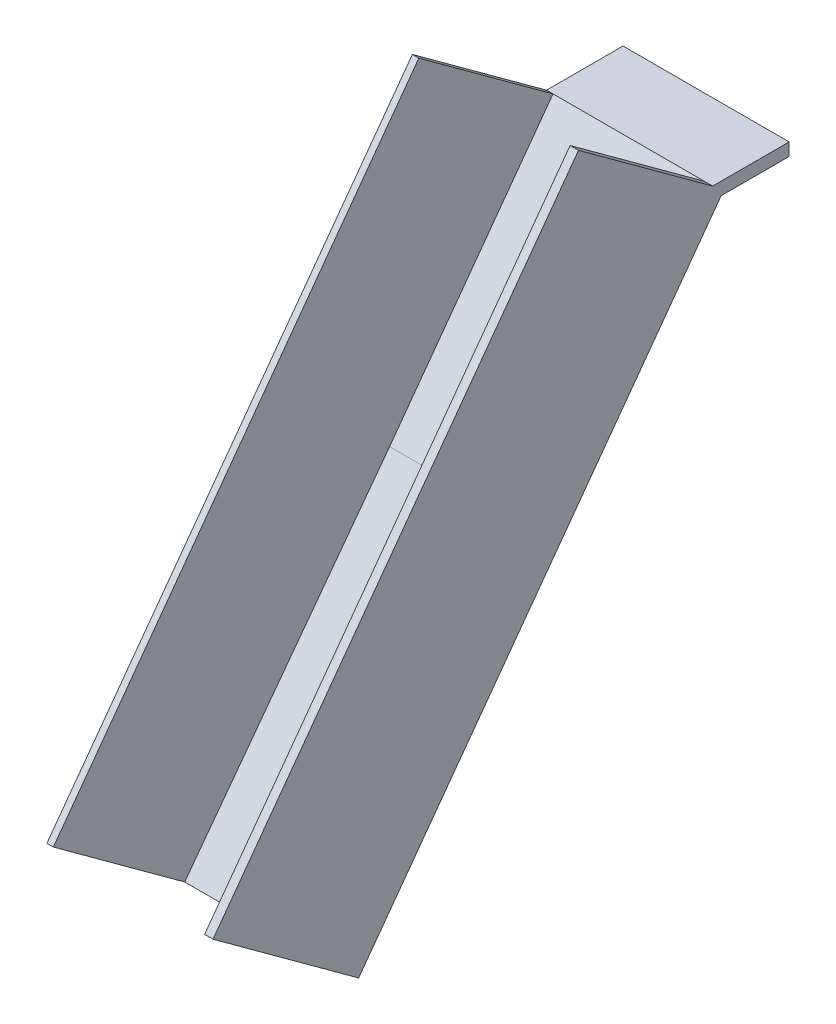
SolidWorks part; units mm, degrees
ref_plane "Front Plane" through (0, 0, 0) normal (0, 0, 1) x (1, 0, 0)
ref_plane "Top Plane" through (0, 0, 0) normal (0, 1, 0) x (1, 0, 0)
ref_plane "Right Plane" through (0, 0, 0) normal (1, 0, 0) x (0, 0, -1)
sketch "Sketch3" plane through (0, 0, 0) normal (1, 0, 0) x (0, 0, -1)
  line L0 (0, 0) -> (39.3483, 53.8717)
  line L1 (39.3483, 53.8717) -> (57.7559, 53.8717)
  line L2 (57.7559, 53.8717) -> (57.7559, 50.8319)
  line L3 (57.7559, 50.8319) -> (41.3748, 50.8319)
  line L4 (41.3748, 50.8319) -> (-45.8836, -68.6334)
  line L5 (-45.8836, -68.6334) -> (-49.3292, -66.1167)
  line L6 (-49.3292, -66.1167) -> (0, 0)
extrude "Boss-Extrude1" add sketch "Sketch3" along normal blind 40
sketch "Sketch4" plane through (0, 0, 0) normal (0, 0.5898, 0.8075) x (1, 0, 0)
  line L0 (0, 66.7117) -> (1.5603, 66.7117)
  line L1 (40, 66.7117) -> (0, 66.7117) construction
  line L2 (1.5603, 66.7117) -> (1.5603, -82.4869)
  line L3 (40, -82.4869) -> (0, -82.4869) construction
  line L4 (1.5603, -82.4869) -> (0, -82.4869)
  line L5 (0, -82.4869) -> (0, 66.7117)
extrude "Boss-Extrude2" add sketch "Sketch4" along normal blind 40
sketch "Sketch6" plane through (0, 0, 0) normal (0, 0.5898, 0.8075) x (1, 0, 0)
  line L0 (40, 66.7117) -> (37.9727, 66.7117)
  line L1 (40, 66.7117) -> (1.5603, 66.7117) construction
  line L2 (37.9727, 66.7117) -> (37.9727, -82.4869)
  line L3 (40, -82.4869) -> (1.5603, -82.4869) construction
  line L4 (37.9727, -82.4869) -> (40, -82.4869)
  line L5 (40, -82.4869) -> (40, 66.7117)
extrude "Boss-Extrude3" add sketch "Sketch6" along normal blind 40
